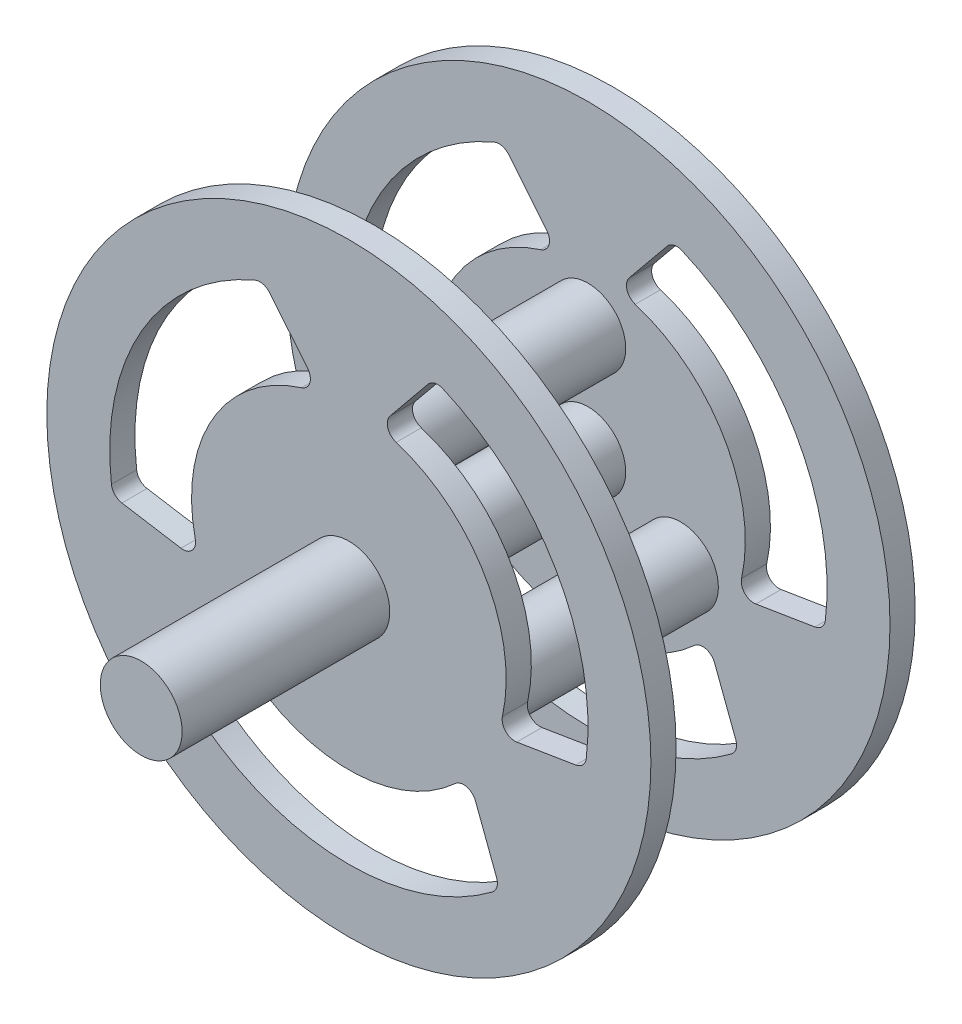
SolidWorks part; units mm, degrees
ref_plane "前视基准面" through (0, 0, 0) normal (0, 0, 1) x (1, 0, 0)
ref_plane "上视基准面" through (0, 0, 0) normal (0, 1, 0) x (1, 0, 0)
ref_plane "右视基准面" through (0, 0, 0) normal (1, 0, 0) x (0, 0, -1)
sketch "草图1" plane through (0, 0, 0) normal (0, 0, 1) x (1, 0, 0)
  line L0 (-11.7396, -14.0428) -> (-10.0576, -9.5976)
  line L1 (11.7396, -14.0428) -> (10.0576, -9.5976)
  line L2 (-18.0313, -3.1454) -> (-13.3406, -3.9113)
  line L3 (-6.2916, 17.1882) -> (-3.283, 13.509)
  line L4 (6.2916, 17.1882) -> (3.283, 13.509)
  line L5 (18.0313, -3.1454) -> (13.3406, -3.9113)
  circle A0 centre (0, 0) radius 24
  arc A1 (-8.4466, -9.2144) -> (8.4466, -9.2144) centre (0, 0) ccw
  arc A2 (-11.4046, -15.1966) -> (11.4046, -15.1966) centre (0, 0) ccw
  arc A3 (11.7396, -14.0428) -> (11.4046, -15.1966) centre (10.8044, -14.3967) cw
  arc A4 (10.0576, -9.5976) -> (8.4466, -9.2144) centre (9.1223, -9.9515) ccw
  arc A5 (-11.7396, -14.0428) -> (-11.4046, -15.1966) centre (-10.8044, -14.3967) ccw
  arc A6 (-10.0576, -9.5976) -> (-8.4466, -9.2144) centre (-9.1223, -9.9515) cw
  arc A7 (-3.7566, 11.9222) -> (-12.2032, -2.7078) centre (0, 0) ccw
  arc A8 (-3.283, 13.509) -> (-3.7566, 11.9222) centre (-4.0571, 12.8759) cw
  arc A9 (-13.3406, -3.9113) -> (-12.2032, -2.7078) centre (-13.1795, -2.9244) ccw
  arc A10 (-18.0313, -3.1454) -> (-18.8629, -2.2784) centre (-17.8701, -2.1585) cw
  arc A11 (-7.4583, 17.4749) -> (-18.8629, -2.2784) centre (0, 0) ccw
  arc A12 (-6.2916, 17.1882) -> (-7.4583, 17.4749) centre (-7.0658, 16.5552) ccw
  arc A13 (12.2032, -2.7078) -> (3.7566, 11.9222) centre (0, 0) ccw
  arc A14 (13.3406, -3.9113) -> (12.2032, -2.7078) centre (13.1795, -2.9244) cw
  arc A15 (3.283, 13.509) -> (3.7566, 11.9222) centre (4.0571, 12.8759) ccw
  arc A16 (6.2916, 17.1882) -> (7.4583, 17.4749) centre (7.0658, 16.5552) cw
  arc A17 (18.8629, -2.2784) -> (7.4583, 17.4749) centre (0, 0) ccw
  arc A18 (18.0313, -3.1454) -> (18.8629, -2.2784) centre (17.8701, -2.1585) ccw
  point P9 (12, -14.7309)
  point P12 (9.5, -8.124)
  point P15 (-12, -14.7309)
  point P18 (-9.5, -8.124)
  point P46 (0, 0)
  dimension "D1" = 48
  dimension "D2" = 25
  dimension "D3" = 38
  dimension "D8" = 1
  dimension "D4" = 9.5
  dimension "D5" = 12
  dimension "D6" = 9.5
  dimension "D7" = 12
  dimension "D9" = 3
extrude "凸台-拉伸1" add sketch "草图1" along normal blind 2
sketch "草图2" plane through (0, 0, 2) normal (0, 0, 1) x (1, 0, 0)
  circle A0 centre (0, 0) radius 3
  circle A1 centre (0, 8.5) radius 3
  circle A2 centre (7.3612, -4.25) radius 3
  circle A3 centre (-7.3612, -4.25) radius 3
  point P11 (0, 0)
  dimension "D1" = 6
  dimension "D2" = 8.5
  dimension "D3" = 3
extrude "凸台-拉伸2" add sketch "草图2" along normal blind 17
sketch "草图3" plane through (0, 0, 19) normal (0, 0, 1) x (1, 0, 0)
  line L2 (-10.0576, -9.5976) -> (-11.7396, -14.0428)
  line L3 (11.7396, -14.0428) -> (10.0576, -9.5976)
  line L4 (-10.0576, -9.5976) -> (-11.7396, -14.0428)
  line L5 (11.7396, -14.0428) -> (10.0576, -9.5976)
  line L6 (6.2916, 17.1882) -> (3.283, 13.509)
  line L7 (13.3406, -3.9113) -> (18.0313, -3.1454)
  line L8 (6.2916, 17.1882) -> (3.283, 13.509)
  line L9 (13.3406, -3.9113) -> (18.0313, -3.1454)
  line L10 (-3.283, 13.509) -> (-6.2916, 17.1882)
  line L11 (-18.0313, -3.1454) -> (-13.3406, -3.9113)
  line L12 (-3.283, 13.509) -> (-6.2916, 17.1882)
  line L13 (-18.0313, -3.1454) -> (-13.3406, -3.9113)
  circle A1 centre (0, 0) radius 24
  circle A2 centre (0, 0) radius 24
  arc A8 (-11.7396, -14.0428) -> (-11.4046, -15.1966) centre (-10.8044, -14.3967) ccw
  arc A9 (-11.4046, -15.1966) -> (11.4046, -15.1966) centre (0, 0) ccw
  arc A10 (11.4046, -15.1966) -> (11.7396, -14.0428) centre (10.8044, -14.3967) ccw
  arc A11 (10.0576, -9.5976) -> (8.4466, -9.2144) centre (9.1223, -9.9515) ccw
  arc A12 (-8.4466, -9.2144) -> (8.4466, -9.2144) centre (0, 0) ccw
  arc A13 (-8.4466, -9.2144) -> (-10.0576, -9.5976) centre (-9.1223, -9.9515) ccw
  arc A14 (-11.7396, -14.0428) -> (-11.4046, -15.1966) centre (-10.8044, -14.3967) ccw
  arc A15 (-11.4046, -15.1966) -> (11.4046, -15.1966) centre (0, 0) ccw
  arc A16 (11.4046, -15.1966) -> (11.7396, -14.0428) centre (10.8044, -14.3967) ccw
  arc A17 (10.0576, -9.5976) -> (8.4466, -9.2144) centre (9.1223, -9.9515) ccw
  arc A18 (-8.4466, -9.2144) -> (8.4466, -9.2144) centre (0, 0) ccw
  arc A19 (-8.4466, -9.2144) -> (-10.0576, -9.5976) centre (-9.1223, -9.9515) ccw
  arc A20 (3.283, 13.509) -> (3.7566, 11.9222) centre (4.0571, 12.8759) ccw
  arc A21 (12.2032, -2.7078) -> (3.7566, 11.9222) centre (0, 0) ccw
  arc A22 (12.2032, -2.7078) -> (13.3406, -3.9113) centre (13.1795, -2.9244) ccw
  arc A23 (18.0313, -3.1454) -> (18.8629, -2.2784) centre (17.8701, -2.1585) ccw
  arc A24 (18.8629, -2.2784) -> (7.4583, 17.4749) centre (0, 0) ccw
  arc A25 (7.4583, 17.4749) -> (6.2916, 17.1882) centre (7.0658, 16.5552) ccw
  arc A26 (3.283, 13.509) -> (3.7566, 11.9222) centre (4.0571, 12.8759) ccw
  arc A27 (12.2032, -2.7078) -> (3.7566, 11.9222) centre (0, 0) ccw
  arc A28 (12.2032, -2.7078) -> (13.3406, -3.9113) centre (13.1795, -2.9244) ccw
  arc A29 (18.0313, -3.1454) -> (18.8629, -2.2784) centre (17.8701, -2.1585) ccw
  arc A30 (18.8629, -2.2784) -> (7.4583, 17.4749) centre (0, 0) ccw
  arc A31 (7.4583, 17.4749) -> (6.2916, 17.1882) centre (7.0658, 16.5552) ccw
  arc A32 (-6.2916, 17.1882) -> (-7.4583, 17.4749) centre (-7.0658, 16.5552) ccw
  arc A33 (-7.4583, 17.4749) -> (-18.8629, -2.2784) centre (0, 0) ccw
  arc A34 (-18.8629, -2.2784) -> (-18.0313, -3.1454) centre (-17.8701, -2.1585) ccw
  arc A35 (-13.3406, -3.9113) -> (-12.2032, -2.7078) centre (-13.1795, -2.9244) ccw
  arc A36 (-3.7566, 11.9222) -> (-12.2032, -2.7078) centre (0, 0) ccw
  arc A37 (-3.7566, 11.9222) -> (-3.283, 13.509) centre (-4.0571, 12.8759) ccw
  arc A38 (-6.2916, 17.1882) -> (-7.4583, 17.4749) centre (-7.0658, 16.5552) ccw
  arc A39 (-7.4583, 17.4749) -> (-18.8629, -2.2784) centre (0, 0) ccw
  arc A40 (-18.8629, -2.2784) -> (-18.0313, -3.1454) centre (-17.8701, -2.1585) ccw
  arc A41 (-13.3406, -3.9113) -> (-12.2032, -2.7078) centre (-13.1795, -2.9244) ccw
  arc A42 (-3.7566, 11.9222) -> (-12.2032, -2.7078) centre (0, 0) ccw
  arc A43 (-3.7566, 11.9222) -> (-3.283, 13.509) centre (-4.0571, 12.8759) ccw
  dimension "D1" = 0
  dimension "D2" = 0
  dimension "D3" = 0
  dimension "D4" = 0
extrude "凸台-拉伸3" add sketch "草图3" along normal blind 2
sketch "草图4" plane through (0, 0, 21) normal (0, 0, 1) x (1, 0, 0)
  circle A0 centre (0, 0) radius 3.25
  dimension "D1" = 6.5
extrude "凸台-拉伸4" add sketch "草图4" along normal blind 16.5
